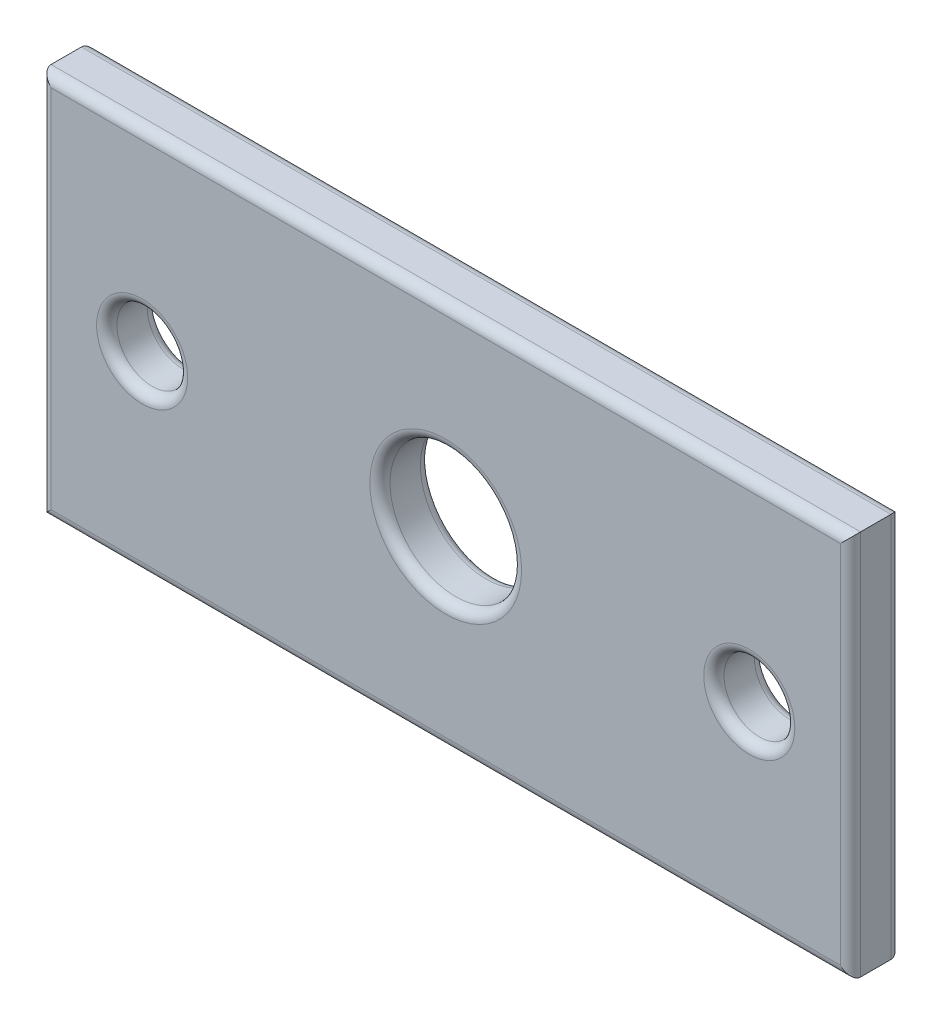
SolidWorks part; units mm, degrees
ref_plane "Front Plane" through (0, 0, 0) normal (0, 0, 1) x (1, 0, 0)
ref_plane "Top Plane" through (0, 0, 0) normal (0, 1, 0) x (1, 0, 0)
ref_plane "Right Plane" through (0, 0, 0) normal (1, 0, 0) x (0, 0, -1)
sketch "Sketch2" plane through (0, 0, 0) normal (0, 0, 1) x (1, 0, 0)
  line L1 (0, 0) -> (80, 0)
  line L2 (0, 0) -> (0, -38.1)
  line L3 (0, -38.1) -> (80, -38.1)
  line L4 (80, 0) -> (80, -38.1)
  circle A0 centre (40, -19.05) radius 10.5
  circle A1 centre (10, -19.05) radius 3.5
  circle A2 centre (70, -19.05) radius 3.5
  circle A3 centre (10, -19.05) radius 5
  circle A4 centre (70, -19.05) radius 5
  circle A5 centre (40, -19.05) radius 6.5
  dimension "D6" = 21
  dimension "D7" = 7
  dimension "D9" = 10
  dimension "D12" = 13
  dimension "D1" = 80
  dimension "D2" = 38.1
  dimension "D3" = 19.05
  dimension "D4" = 10
  dimension "D5" = 60
  dimension "D8" = 0
  dimension "D10" = 0
  dimension "D11" = 40
extrude "Boss-Extrude1" add sketch "Sketch2" along normal blind 5 contours L4 L1 L2 L3 A4 A3 A0 | A0 A5 | A3 A1 | A4 A2
fillet "Fillet1" radius 1 14 edges at (73.5, -19.05, 5) (73.5, -19.05, 0) (13.5, -19.05, 5) (13.5, -19.05, 0) (46.5, -19.05, 5) (46.5, -19.05, 0) (40, -38.1, 0) (40, -38.1, 5) (0, -19.05, 0) (0, -19.05, 5) (40, 0, 0) (40, 0, 5) (80, -19.05, 0) (80, -19.05, 5)
